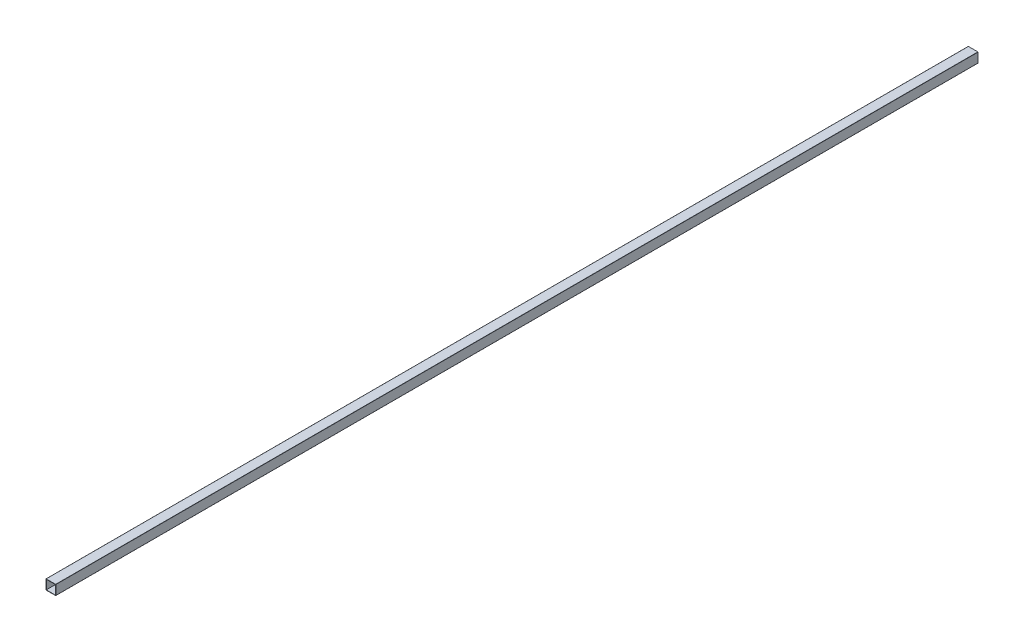
SolidWorks part; units mm, degrees
material "AISI 1035 Acero (SS)"
ref_plane "Alzado" through (0, 0, 0) normal (0, 0, 1) x (1, 0, 0)
ref_plane "Planta" through (0, 0, 0) normal (0, 1, 0) x (1, 0, 0)
ref_plane "Vista lateral" through (0, 0, 0) normal (1, 0, 0) x (0, 0, -1)
sketch "Croquis1" plane through (0, 0, 0) normal (0, 0, 1) x (1, 0, 0)
  line L0 (-29.86, -29.86) -> (-29.86, 29.86)
  line L1 (-30.75, -31.75) -> (30.75, -31.75)
  line L2 (-31.75, -30.75) -> (-31.75, 30.75)
  line L3 (-30.75, 31.75) -> (30.75, 31.75)
  line L4 (31.75, -30.75) -> (31.75, 30.75)
  line L5 (-31.75, -31.75) -> (31.75, 31.75) construction
  line L6 (-31.75, 31.75) -> (31.75, -31.75) construction
  line L7 (-29.86, 29.86) -> (29.86, 29.86)
  line L8 (29.86, -29.86) -> (29.86, 29.86)
  line L9 (-29.86, -29.86) -> (29.86, -29.86)
  line L10 (-31.75, -31.75) -> (31.75, -31.75) construction
  line L11 (-31.75, -31.75) -> (-31.75, 31.75) construction
  line L12 (31.75, -31.75) -> (31.75, 31.75) construction
  line L13 (-31.75, 31.75) -> (31.75, 31.75) construction
  arc A0 (-30.75, -31.75) -> (-31.75, -30.75) centre (-30.75, -30.75) cw
  arc A1 (30.75, -31.75) -> (31.75, -30.75) centre (30.75, -30.75) ccw
  arc A2 (30.75, 31.75) -> (31.75, 30.75) centre (30.75, 30.75) cw
  arc A3 (-31.75, 30.75) -> (-30.75, 31.75) centre (-30.75, 30.75) cw
  point P0 (0, 0)
  dimension "D2" = 1
  dimension "D1" = 63.5
  dimension "D3" = 1.89
extrude "Saliente-Extruir1" add sketch "Croquis1" along normal blind 6000
